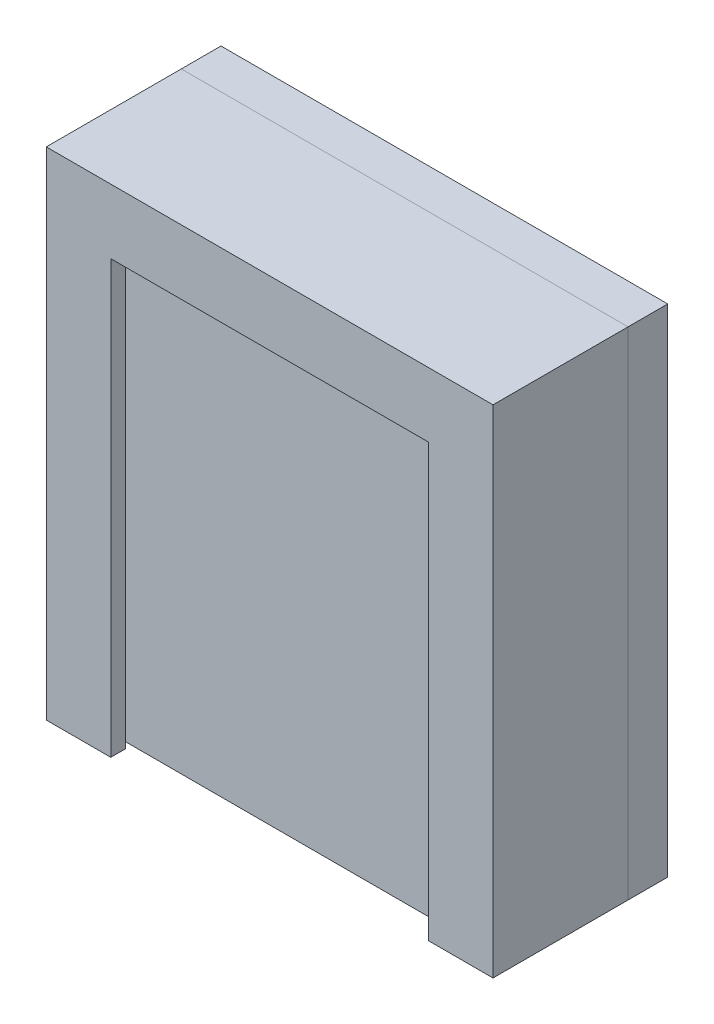
SolidWorks part; units mm, degrees
ref_plane "Plano frontal" through (0, 0, 0) normal (0, 0, 1) x (1, 0, 0)
ref_plane "Plano superior" through (0, 0, 0) normal (0, 1, 0) x (1, 0, 0)
ref_plane "Plano direito" through (0, 0, 0) normal (1, 0, 0) x (0, 0, -1)
sketch "Esboço1" plane through (0, 0, 0) normal (0, 0, 1) x (1, 0, 0)
  line L1 (45, -50) -> (-45, -50)
  line L2 (45, -50) -> (45, 50)
  line L3 (45, 50) -> (-45, 50)
  line L4 (-45, -50) -> (-45, 50)
  line L5 (45, -50) -> (-45, 50) construction
  line L6 (45, 50) -> (-45, -50) construction
  point P0 (0, 0)
  dimension "100" = 90
  dimension "D2" = 100
extrude "Ressalto-extrusão1" add sketch "Esboço1" along normal blind 5
sketch "Esboço2" plane through (0, 0, 5) normal (0, 0, 1) x (1, 0, 0)
  line L4 (-45, 50) -> (-45, -50)
  line L5 (-45, -50) -> (45, -50)
  line L6 (45, -50) -> (45, 50)
  line L7 (45, 50) -> (-45, 50)
  line L8 (-45, 50) -> (-45, -50)
  line L9 (-45, -50) -> (45, -50)
  line L10 (45, -50) -> (45, 50)
  line L11 (45, 50) -> (-45, 50)
  line L12 (37, -42) -> (37, -50)
  line L13 (-37, -42) -> (-37, -50)
  line L16 (-37, 42) -> (-37, -42)
  line L17 (-37, -42) -> (37, -42)
  line L18 (37, -42) -> (37, 42)
  line L19 (37, 42) -> (-37, 42)
  line L20 (-37, 42) -> (-37, -42)
  line L22 (37, -42) -> (37, 42)
  line L23 (37, 42) -> (-37, 42)
  line M9 (-45, 50) -> (-45, -50)
  line M10 (-45, -50) -> (45, -50)
  line M11 (45, -50) -> (45, 50)
  line M12 (45, 50) -> (-45, 50)
  dimension "D1" = 0
  dimension "D2" = 8
extrude "Ressalto-extrusão2" add sketch "Esboço2" along normal blind 1.2 contours L23 L22 L12 L9 L13 L20 M11 M12 M9 M10
sketch "Esboço3" plane through (0, 0, 6.2) normal (0, 0, 1) x (1, 0, 0)
  line L8 (-37, 42) -> (37, 42)
  line L9 (37, 42) -> (37, -50)
  line L10 (37, -50) -> (45, -50)
  line L11 (45, -50) -> (45, 50)
  line L12 (45, 50) -> (-45, 50)
  line L13 (-45, 50) -> (-45, -50)
  line L14 (-45, -50) -> (-37, -50)
  line L15 (-37, -50) -> (-37, 42)
  line L18 (37, -50) -> (45, -50)
  line L19 (45, -50) -> (45, 50)
  line L20 (45, 50) -> (-45, 50)
  line L24 (-45, 50) -> (-45, -50) construction
  line L25 (-45, 50) -> (-45, -50)
  line L26 (-45, -50) -> (-37, -50) construction
  line L27 (-45, -50) -> (-37, -50)
  line L28 (-37, -50) -> (-32, -50)
  line L29 (-32, -50) -> (-32, 37)
  line L30 (-32, 37) -> (32, 37)
  line L31 (32, 37) -> (32, -50)
  line L32 (32, -50) -> (37, -50)
  line L33 (-37, 42) -> (-37, -50) construction
  line L34 (37, 42) -> (-37, 42) construction
  line L35 (37, -50) -> (37, 42) construction
  dimension "D2" = 5
  dimension "D3" = 5
  dimension "D4" = 5
  dimension "D1" = 0
extrude "Ressalto-extrusão3" add sketch "Esboço3" along normal blind 3
sketch "Esboço4" plane through (0, 0, 0) normal (1, 0, 0) x (0, 0, -1)
  line L0 (-5, -50) -> (-17.45, -50) construction
  line L2 (-9.2, -50) -> (-6.2, -50) construction
  line L3 (-5, 42) -> (-5, -50) construction
  circle A0 centre (0, -50) radius 5
  dimension "D1" = 10
sketch "Esboço5" plane through (0, 0, 0) normal (0, 0, -1) x (-1, 0, 0)
  line L0 (40, -45) -> (-40, -45)
  line L1 (45, 50) -> (-45, 50)
  line L2 (45, 50) -> (45, -50)
  line L3 (45, -50) -> (-45, -50)
  line L4 (-45, 50) -> (-45, -50)
  line L5 (45, 50) -> (-45, -50) construction
  line L6 (45, -50) -> (-45, 50) construction
  line L7 (-40, 45) -> (-40, -45)
  line L8 (40, 45) -> (-40, 45)
  line L9 (40, 45) -> (40, -45)
  point P0 (0, 0)
  dimension "D1" = 5
extrude "Ressalto-extrusão5" add sketch "Esboço5" along normal blind 18
sketch "Esboço7" plane through (0, -50, 0) normal (0, -1, 0) x (1, 0, 0)
  line L0 (45, 9.2) -> (45, -18) construction
  line L1 (-45, 9.2) -> (45, 9.2)
  line L2 (-45, 9.2) -> (-45, 5)
  line L3 (-45, 5) -> (45, 5)
  line L4 (45, 9.2) -> (45, 5)
  line L5 (-37, 5) -> (37, 5) construction
  point P7 (0, 0)
extrude "Corte-extrusão2" [suppressed] cut sketch "Esboço7" against normal blind 184
sketch "Esboço8" plane through (0, 0, -18) normal (0, 0, -1) x (-1, 0, 0)
  line L0 (45, -50) -> (42.3871, -50)
  line L1 (-45, -50) -> (45, -50) construction
  line L2 (45, -50) -> (45, 50) construction
  line L3 (45, -50) -> (45, 50)
  line L4 (45, 50) -> (-45, 50) construction
  line L5 (45, 50) -> (-45, 50)
  line L6 (-45, 50) -> (-45, -50) construction
  line L7 (-45, 50) -> (-45, -50)
  line L8 (42.5, -50) -> (42.5, 47.5)
  line L9 (42.5, 47.5) -> (-42.5, 47.5)
  line L10 (-42.5, 47.5) -> (-42.5, -50)
  line M4 (-45, 50) -> (-45, -50)
  line M5 (-45, -50) -> (45, -50)
  line M6 (45, -50) -> (45, 50)
  line M7 (45, 50) -> (-45, 50)
  dimension "D1" = 2.5
extrude "Ressalto-extrusão6" add sketch "Esboço8" along normal blind 4 separate body contours L10 L9 L8 L0 M6 M7 M4 M5
sketch "Esboço9" plane through (0, 0, -22) normal (0, 0, -1) x (-1, 0, 0)
  line L0 (40, -45) -> (40, 45) construction
  line L1 (40, 45) -> (-40, 45) construction
  line L2 (-40, 45) -> (-40, -45) construction
  line L3 (40, -45) -> (40, 45)
  line L4 (-45, 50) -> (-45, -50)
  line L5 (-45, -50) -> (45, -50)
  line L6 (45, -50) -> (45, 50)
  line L7 (45, 50) -> (-45, 50)
  line L8 (-42.5, -50) -> (-42.5, 47.5)
  line L9 (-42.5, 47.5) -> (42.5, 47.5)
  line L10 (42.5, 47.5) -> (42.5, -50)
  line L11 (42.5, -50) -> (45, -50)
  line L12 (45, -50) -> (45, 50)
  line L13 (45, 50) -> (-45, 50)
  line L14 (-45, 50) -> (-45, -50)
  line L15 (-45, -50) -> (-42.5, -50)
  line L16 (-42.5, -50) -> (-42.5, 47.5)
  line L17 (-42.5, 47.5) -> (42.5, 47.5)
  line L18 (42.5, 47.5) -> (42.5, -50)
  line L19 (42.5, -50) -> (45, -50)
  line L20 (45, -50) -> (45, 50)
  line L21 (45, 50) -> (-45, 50)
  line L22 (-45, 50) -> (-45, -50)
  line L23 (-45, -50) -> (-42.5, -50)
  line L24 (-45, 50) -> (-45, -50)
  line L25 (-45, -50) -> (45, -50)
  line L26 (45, -50) -> (45, 50)
  line L27 (45, 50) -> (-45, 50)
  line L28 (40, 45) -> (-40, 45)
  line L29 (-40, 45) -> (-40, -45)
  line L30 (-40, -45) -> (-40, -50)
  line L31 (-40, -50) -> (-42.5, -50)
  line L32 (-40, -45) -> (-42.5, -50)
  line L33 (42.5, -50) -> (40, -45)
  line M13 (-42.5, -50) -> (-42.5, 47.5)
  line M14 (-42.5, 47.5) -> (42.5, 47.5)
  line M15 (42.5, 47.5) -> (42.5, -50)
  line M16 (42.5, -50) -> (45, -50)
  line M17 (45, -50) -> (45, 50)
  line M18 (45, 50) -> (-45, 50)
  line M19 (-45, 50) -> (-45, -50)
  line M20 (-45, -50) -> (-42.5, -50)
  dimension "D1" = 0
  dimension "D2" = 0
extrude "Ressalto-extrusão7" add sketch "Esboço9" along normal blind 4 contours M20 M13 M14 M15 M16 M17 M18 M19 | L33 L32 L29 L28 L3 M15 M14 M13
sketch "Esboço10" plane through (0, -45, 0) normal (0, 1, 0) x (1, 0, 0)
  line L4 (-40, 0) -> (40, 0)
  line L5 (40, 0) -> (40, 18)
  line L6 (40, 18) -> (-40, 18)
  line L7 (-40, 18) -> (-40, 0)
  line L8 (-40, 0) -> (40, 0)
  line L9 (40, 0) -> (40, 18)
  line L10 (40, 18) -> (-40, 18)
  line L11 (-40, 18) -> (-40, 0)
  dimension "D1" = 0
extrude "Corte-extrusão3" cut sketch "Esboço10" against normal blind 14
